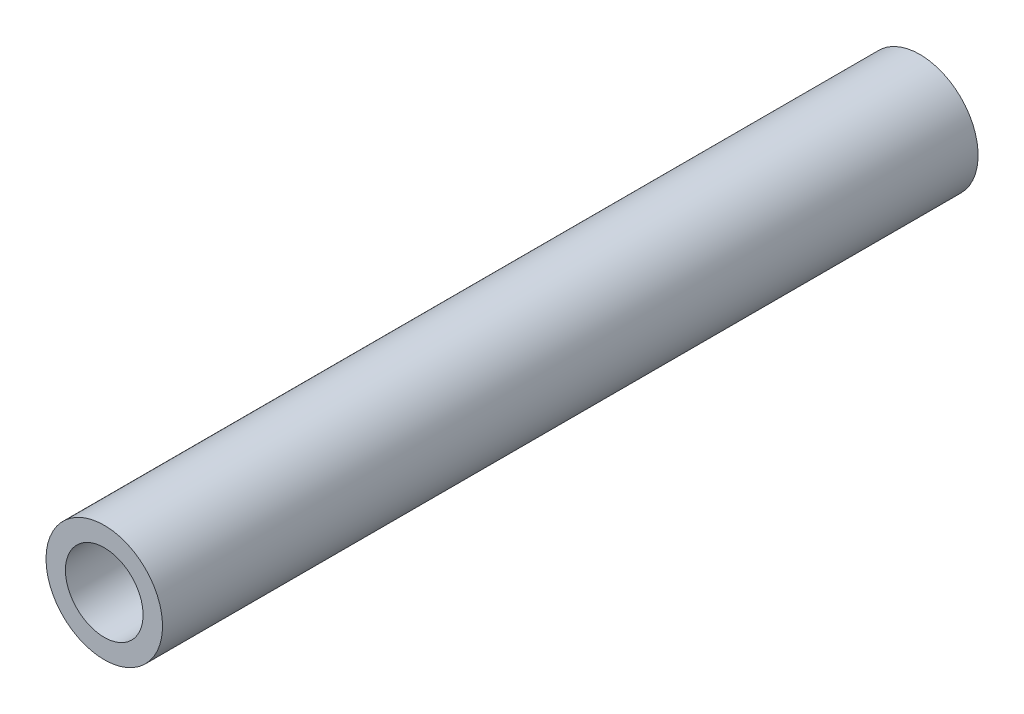
SolidWorks part; units mm, degrees
material "C-Fibra di vetro"
ref_plane "Piano frontale" through (0, 0, 0) normal (0, 0, 1) x (1, 0, 0)
ref_plane "Piano superiore" through (0, 0, 0) normal (0, 1, 0) x (1, 0, 0)
ref_plane "Piano destro" through (0, 0, 0) normal (1, 0, 0) x (0, 0, -1)
sketch "Schizzo2" plane through (0, 0, 0) normal (0, 0, 1) x (1, 0, 0)
  circle A0 centre (13, -54.5) radius 3
  circle A1 centre (13, -54.5) radius 2
  dimension "D1" = 6
  dimension "D2" = 1
extrude "Estrusione-Estrusione1" add sketch "Schizzo2" along normal up to surface (42 mm away)
